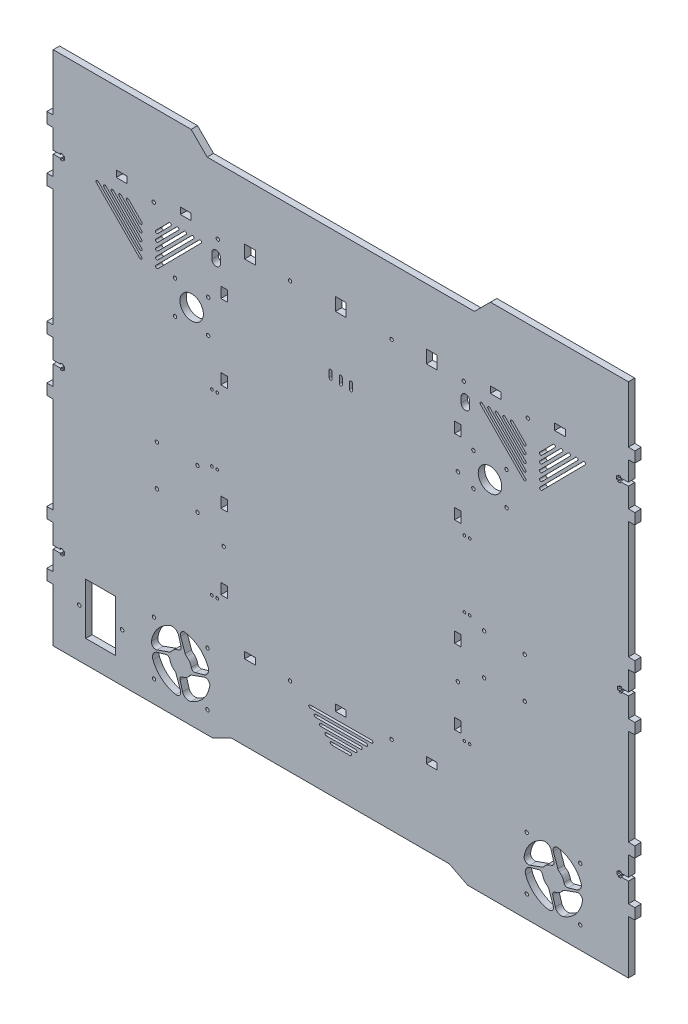
SolidWorks part; units mm, degrees
material "Клен"
ref_plane "Front" through (0, 0, 0) normal (0, 0, 1) x (1, 0, 0)
ref_plane "Top" through (0, 0, 0) normal (0, 1, 0) x (1, 0, 0)
ref_plane "Right" through (0, 0, 0) normal (1, 0, 0) x (0, 0, -1)
sketch "Эскиз1" plane through (0, 0, 0) normal (0, 0, 1) x (1, 0, 0)
  line L3 (1048.7554, 41.5559) -> (1198.2753, 41.5559)
  line L12 (1586.7554, 42.2299) -> (1586.7554, 41.5559)
  line L13 (1397.7554, 444.5559) -> (1407.7554, 444.5559)
  line L14 (1407.7554, 444.5559) -> (1407.7554, 456.6559)
  line L15 (1407.7554, 456.6559) -> (1397.7554, 456.6559)
  line L16 (1397.7554, 456.6559) -> (1397.7554, 444.5559)
  line L17 (1048.7554, 42.2256) -> (1048.7554, 41.5559)
  line L18 (1197.1554, 434.4743) -> (1197.1554, 429.1914)
  line L19 (1503.9666, 426.2291) -> (1516.2724, 438.6716)
  line L20 (1546.3337, 437.0699) -> (1505.9003, 396.1873)
  line L21 (1227.7554, 444.5559) -> (1237.7554, 444.5559)
  line L22 (1237.7554, 444.5559) -> (1237.7554, 456.6559)
  line L23 (1237.7554, 456.6559) -> (1227.7554, 456.6559)
  line L24 (1227.7554, 456.6559) -> (1227.7554, 444.5559)
  line L25 (1312.7554, 444.5559) -> (1322.7554, 444.5559)
  line L26 (1322.7554, 444.5559) -> (1322.7554, 456.6559)
  line L27 (1322.7554, 456.6559) -> (1312.7554, 456.6559)
  line L28 (1312.7554, 456.6559) -> (1312.7554, 444.5559)
  line L38 (1525.1209, 436.9527) -> (1505.7831, 417.4001)
  line L41 (1504.0838, 405.0162) -> (1537.4853, 438.7888)
  line L43 (1504.1228, 397.9452) -> (1544.5562, 438.8279)
  line L44 (1504.0056, 419.1581) -> (1523.3433, 438.7107)
  line L48 (1167.7554, 450.5559) -> (1177.7554, 450.5559)
  line L49 (1177.7554, 450.5559) -> (1177.7554, 456.6559)
  line L50 (1177.7554, 456.6559) -> (1167.7554, 456.6559)
  line L51 (1167.7554, 456.6559) -> (1167.7554, 450.5559)
  line L52 (1518.0499, 436.9136) -> (1505.7441, 424.4711)
  line L53 (1532.1918, 436.9918) -> (1505.8222, 410.3292)
  line L54 (1539.2628, 437.0308) -> (1505.8613, 403.2582)
  line L55 (1504.0447, 412.0872) -> (1530.4143, 438.7498)
  line L56 (1457.7554, 450.5559) -> (1467.7554, 450.5559)
  line L57 (1467.7554, 450.5559) -> (1467.7554, 456.6559)
  line L58 (1467.7554, 456.6559) -> (1457.7554, 456.6559)
  line L59 (1457.7554, 456.6559) -> (1457.7554, 450.5559)
  line L78 (1131.3881, 397.9452) -> (1090.9547, 438.8279)
  line L80 (1089.1772, 437.0699) -> (1129.6105, 396.1873)
  line L82 (1096.2481, 437.0308) -> (1129.6496, 403.2582)
  line L83 (1131.4271, 405.0162) -> (1098.0256, 438.7888)
  line L84 (1131.4662, 412.0872) -> (1105.0966, 438.7498)
  line L85 (1103.3191, 436.9918) -> (1129.6887, 410.3292)
  line L86 (1131.5052, 419.1581) -> (1112.1675, 438.7107)
  line L87 (1110.39, 436.9527) -> (1129.7277, 417.4001)
  line L88 (1131.5443, 426.2291) -> (1119.2385, 438.6716)
  line L89 (1117.461, 436.9136) -> (1129.7668, 424.4711)
  line L90 (1144.921, 397.9452) -> (1185.3543, 438.8279)
  line L91 (1187.1318, 437.0699) -> (1146.6985, 396.1873)
  line L92 (1397.7554, 120.5559) -> (1407.7554, 120.5559)
  line L93 (1407.7554, 120.5559) -> (1407.7554, 126.6559)
  line L94 (1407.7554, 126.6559) -> (1397.7554, 126.6559)
  line L95 (1397.7554, 126.6559) -> (1397.7554, 120.5559)
  line L96 (1312.7554, 120.5559) -> (1322.7554, 120.5559)
  line L97 (1322.7554, 120.5559) -> (1322.7554, 126.6559)
  line L98 (1322.7554, 126.6559) -> (1312.7554, 126.6559)
  line L99 (1312.7554, 126.6559) -> (1312.7554, 120.5559)
  line L100 (1227.7554, 120.5559) -> (1237.7554, 120.5559)
  line L101 (1237.7554, 120.5559) -> (1237.7554, 126.6559)
  line L102 (1237.7554, 126.6559) -> (1227.7554, 126.6559)
  line L143 (1227.7554, 126.6559) -> (1227.7554, 120.5559)
  line L148 (1079.1628, 110.8776) -> (1079.1628, 62.8776)
  line L154 (1455.45, 437.0308) -> (1488.8515, 403.2582)
  line L159 (1107.1628, 110.8776) -> (1079.1628, 110.8776)
  line L160 (1079.1628, 62.8776) -> (1107.1628, 62.8776)
  line L161 (1107.1628, 62.8776) -> (1107.1628, 110.8776)
  line L162 (1144.8819, 405.0162) -> (1178.2834, 438.7888)
  line L163 (1180.0609, 437.0308) -> (1146.6594, 403.2582)
  line L164 (1172.9899, 436.9918) -> (1146.6203, 410.3292)
  line L165 (1144.8428, 412.0872) -> (1171.2124, 438.7498)
  line L166 (1144.8038, 419.1581) -> (1164.1415, 438.7107)
  line L167 (1165.919, 436.9527) -> (1146.5813, 417.4001)
  line L168 (1158.848, 436.9136) -> (1146.5422, 424.4711)
  line L169 (1144.7647, 426.2291) -> (1157.0705, 438.6716)
  line L170 (1205.1554, 429.1914) -> (1205.1554, 434.4743)
  line L171 (1430.3554, 429.1914) -> (1430.3554, 434.4743)
  line L172 (1326.6292, 91.6177) -> (1309.1294, 91.521)
  line L173 (1309.1156, 94.021) -> (1326.6154, 94.1176)
  line L174 (1331.6015, 96.6452) -> (1304.1019, 96.4933)
  line L175 (1304.0881, 98.9933) -> (1331.5877, 99.1452)
  line L176 (1336.5738, 101.6728) -> (1299.0744, 101.4656)
  line L177 (1299.0605, 103.9656) -> (1336.56, 104.1727)
  line L178 (1289.0054, 113.9102) -> (1346.5046, 114.2278)
  line L179 (1346.5184, 111.7279) -> (1289.0193, 111.4102)
  line L180 (1341.5461, 106.7003) -> (1294.0468, 106.4379)
  line L181 (1294.033, 108.9379) -> (1341.5323, 109.2003)
  line L182 (1490.629, 405.0162) -> (1457.2275, 438.7888)
  line L183 (1448.379, 437.0699) -> (1488.8124, 396.1873)
  line L184 (1469.5919, 436.9527) -> (1488.9296, 417.4001)
  line L185 (1476.6629, 436.9136) -> (1488.9687, 424.4711)
  line L186 (1490.5899, 397.9452) -> (1450.1565, 438.8279)
  line L187 (1490.7071, 419.1581) -> (1471.3694, 438.7107)
  line L188 (1462.521, 436.9918) -> (1488.8906, 410.3292)
  line L189 (1490.7462, 426.2291) -> (1478.4404, 438.6716)
  line L198 (1530.3174, 86.3769) -> (1538.4752, 88.7337)
  line L199 (1494.5571, 86.9094) -> (1506.2002, 91.0661)
  line L200 (1517.0418, 100.6255) -> (1514.685, 108.7833)
  line L201 (1502.7664, 87.3542) -> (1494.6086, 84.9974)
  line L202 (1538.538, 86.8062) -> (1526.8948, 82.6495)
  line L203 (1516.0532, 73.09) -> (1518.4101, 64.9322)
  line L204 (1516.4826, 64.8695) -> (1512.3258, 76.5127)
  line L205 (1516.6012, 108.8616) -> (1520.758, 97.2184)
  line L210 (1215.2753, 50.2559) -> (1198.2753, 41.5559)
  line L268 (1215.2753, 50.2559) -> (1419.2753, 50.2559)
  line L269 (1419.2753, 50.2559) -> (1436.2753, 41.5559)
  line L270 (1436.2753, 41.5559) -> (1586.7554, 41.5559)
  line L271 (1490.6681, 412.0872) -> (1464.2985, 438.7498)
  line L302 (1527.7554, 456.6559) -> (1517.7554, 456.6559)
  line L303 (1517.7554, 450.5559) -> (1527.7554, 450.5559)
  line L304 (1517.7554, 456.6559) -> (1517.7554, 450.5559)
  line L305 (1527.7554, 450.5559) -> (1527.7554, 456.6559)
  line L306 (1117.7554, 450.5559) -> (1117.7554, 456.6559)
  line L307 (1107.7554, 456.6559) -> (1107.7554, 450.5559)
  line L308 (1117.7554, 456.6559) -> (1107.7554, 456.6559)
  line L309 (1107.7554, 450.5559) -> (1117.7554, 450.5559)
  line L310 (1167.825, 64.8695) -> (1163.6683, 76.5127)
  line L331 (1438.3554, 434.4743) -> (1438.3554, 429.1914)
  line L332 (1592.7554, 85.0176) -> (1592.7554, 537.1765) construction
  line L333 (989.7428, 524.5559) -> (1177.7554, 524.5559) construction
  line L335 (1048.7554, 524.5559) -> (1177.7554, 524.5559)
  line L337 (1048.7554, 524.5559) -> (1048.7554, 471.6559)
  line L338 (1586.7554, 524.5559) -> (1586.7554, 471.6484)
  line L339 (1442.7554, 509.5559) -> (1457.7554, 524.5559)
  line L342 (1192.7554, 509.5559) -> (1442.7554, 509.5559)
  line L346 (1192.7554, 509.5559) -> (1177.7554, 524.5559)
  line L348 (1592.7554, 461.5645) -> (1586.7554, 461.472)
  line L349 (1457.7554, 524.5559) -> (1617.7234, 524.5559) construction
  line L350 (1457.7554, 524.5559) -> (1586.7554, 524.5559)
  line L358 (1059.2554, 440.0059) -> (1059.2554, 443.1059)
  line L359 (1057.7554, 438.8059) -> (1057.7554, 440.0059)
  line L361 (1057.7554, 270.0059) -> (1059.2554, 270.0059)
  line L362 (1055.5554, 270.0059) -> (1055.5554, 268.8059)
  line L363 (1430.3554, 401.4559) -> (1430.3554, 411.4559)
  line L364 (1430.3554, 411.4559) -> (1424.2554, 411.4559)
  line L365 (1424.2554, 411.4559) -> (1424.2554, 401.4559)
  line L366 (1424.2554, 401.4559) -> (1430.3554, 401.4559)
  line L367 (1430.3554, 331.4559) -> (1430.3554, 341.4559)
  line L368 (1430.3554, 341.4559) -> (1424.2554, 341.4559)
  line L369 (1424.2554, 341.4559) -> (1424.2554, 331.4559)
  line L370 (1424.2554, 331.4559) -> (1430.3554, 331.4559)
  line L371 (1430.3554, 231.4559) -> (1430.3554, 241.4559)
  line L372 (1430.3554, 241.4559) -> (1424.2554, 241.4559)
  line L373 (1424.2554, 241.4559) -> (1424.2554, 231.4559)
  line L374 (1424.2554, 231.4559) -> (1430.3554, 231.4559)
  line L375 (1424.2554, 171.4559) -> (1424.2554, 161.4559)
  line L376 (1424.2554, 161.4559) -> (1430.3554, 161.4559)
  line L377 (1430.3554, 161.4559) -> (1430.3554, 171.4559)
  line L378 (1430.3554, 171.4559) -> (1424.2554, 171.4559)
  line L379 (1205.5754, 161.4559) -> (1211.6754, 161.4559)
  line L380 (1211.6754, 161.4559) -> (1211.6754, 171.4559)
  line L381 (1205.5754, 171.4559) -> (1205.5754, 161.4559)
  line L382 (1211.6754, 171.4559) -> (1205.5754, 171.4559)
  line L383 (1211.6754, 231.4559) -> (1211.6754, 241.4559)
  line L384 (1211.6754, 241.4559) -> (1205.5754, 241.4559)
  line L385 (1205.5754, 241.4559) -> (1205.5754, 231.4559)
  line L386 (1205.5754, 231.4559) -> (1211.6754, 231.4559)
  line L387 (1205.5754, 331.4559) -> (1211.6754, 331.4559)
  line L388 (1211.6754, 331.4559) -> (1211.6754, 341.4559)
  line L389 (1205.5754, 341.4559) -> (1205.5754, 331.4559)
  line L390 (1211.6754, 341.4559) -> (1205.5754, 341.4559)
  line L391 (1205.5754, 401.4559) -> (1211.6754, 401.4559)
  line L392 (1211.6754, 401.4559) -> (1211.6754, 411.4559)
  line L393 (1211.6754, 411.4559) -> (1205.5754, 411.4559)
  line L394 (1205.5754, 411.4559) -> (1205.5754, 401.4559)
  line L395 (1145.8995, 86.9094) -> (1157.5427, 91.0661)
  line L396 (1189.8804, 86.8062) -> (1178.2373, 82.6495)
  line L397 (1167.3957, 73.09) -> (1169.7525, 64.9322)
  line L398 (1154.1089, 87.3542) -> (1145.951, 84.9974)
  line L399 (1181.6599, 86.3769) -> (1189.8177, 88.7337)
  line L400 (1167.9437, 108.8616) -> (1172.1004, 97.2184)
  line L414 (1057.7554, 118.8059) -> (1057.7554, 120.0059)
  line L415 (1168.3843, 100.6255) -> (1166.0274, 108.7833)
  line L416 (1317.7554, 12.4246) -> (1317.7554, 537.1765) construction
  line L417 (1586.7554, 537.1765) -> (1586.7554, 12.4246) construction
  line L418 (1048.7554, 537.1765) -> (1048.7554, -11.6164) construction
  line L419 (1042.7554, 91.5559) -> (1042.7554, 101.5559)
  line L422 (1048.7554, 123.1059) -> (1048.7554, 141.4559)
  line L426 (1059.2554, 123.1059) -> (1057.7554, 123.1059)
  line L427 (1057.7554, 274.3059) -> (1055.5554, 274.3059)
  line L428 (1325.8554, 394.0442) -> (1325.8554, 388.0442)
  line L429 (1328.6554, 388.0442) -> (1328.6554, 394.0442)
  line L430 (1042.7554, 101.5559) -> (1048.7554, 101.6559)
  line L431 (1057.7554, 120.0059) -> (1059.2554, 120.0059)
  line L432 (1316.3554, 394.0442) -> (1316.3554, 388.0442)
  line L433 (1319.1554, 388.0442) -> (1319.1554, 394.0442)
  line L434 (1042.7554, 141.5559) -> (1042.7554, 151.5559)
  line L435 (1042.7554, 301.5559) -> (1048.7554, 301.6559)
  line L436 (1306.8554, 394.0442) -> (1306.8554, 388.0442)
  line L437 (1309.6554, 388.0442) -> (1309.6554, 394.0442)
  line L438 (1055.5554, 120.0059) -> (1055.5554, 118.8059)
  line L439 (1048.7554, 411.4559) -> (1042.7554, 411.5559)
  line L440 (1055.5554, 444.3059) -> (1055.5554, 443.1059)
  line L441 (1057.7554, 124.3059) -> (1055.5554, 124.3059)
  line L442 (1055.5554, 443.1059) -> (1048.7554, 443.1059)
  line L443 (1048.7554, 120.0059) -> (1055.5554, 120.0059)
  line L444 (1042.7554, 241.5559) -> (1042.7554, 251.5559)
  line L445 (1055.5554, 268.8059) -> (1057.7554, 268.8059)
  line L446 (1055.5554, 274.3059) -> (1055.5554, 273.1059)
  line L447 (1048.7554, 461.4559) -> (1042.7554, 461.5559)
  line L448 (1048.7554, 101.6559) -> (1048.7554, 120.0059)
  line L449 (1057.7554, 440.0059) -> (1059.2554, 440.0059)
  line L450 (1048.7554, 251.6559) -> (1048.7554, 270.0059)
  line L451 (1042.7554, 291.5559) -> (1042.7554, 301.5559)
  line L452 (1042.7554, 471.5559) -> (1048.7554, 471.6559)
  line L453 (1059.2554, 443.1059) -> (1057.7554, 443.1059)
  line L454 (1048.7554, 42.2256) -> (1048.7554, 91.4559)
  line L455 (1048.7554, 273.1059) -> (1048.7554, 291.4559)
  line L456 (1055.5554, 440.0059) -> (1055.5554, 438.8059)
  line L457 (1055.5554, 438.8059) -> (1057.7554, 438.8059)
  line L458 (1042.7554, 421.5559) -> (1048.7554, 421.6559)
  line L459 (1048.7554, 443.1059) -> (1048.7554, 461.4559)
  line L460 (1048.7554, 141.4559) -> (1042.7554, 141.5559)
  line L461 (1048.7554, 301.6559) -> (1048.7554, 411.4559)
  line L462 (1048.7554, 91.4559) -> (1042.7554, 91.5559)
  line L463 (1048.7554, 270.0059) -> (1055.5554, 270.0059)
  line L464 (1048.7554, 291.4559) -> (1042.7554, 291.5559)
  line L465 (1059.2554, 120.0059) -> (1059.2554, 123.1059)
  line L466 (1057.7554, 273.1059) -> (1057.7554, 274.3059)
  line L467 (1042.7554, 251.5559) -> (1048.7554, 251.6559)
  line L468 (1059.2554, 273.1059) -> (1057.7554, 273.1059)
  line L469 (1048.7554, 421.6559) -> (1048.7554, 440.0059)
  line L470 (1042.7554, 461.5559) -> (1042.7554, 471.5559)
  line L471 (1057.7554, 268.8059) -> (1057.7554, 270.0059)
  line L472 (1057.7554, 443.1059) -> (1057.7554, 444.3059)
  line L473 (1042.7554, 151.5559) -> (1048.7554, 151.6559)
  line L474 (1059.2554, 270.0059) -> (1059.2554, 273.1059)
  line L475 (1055.5554, 273.1059) -> (1048.7554, 273.1059)
  line L476 (1048.7554, 151.6559) -> (1048.7554, 241.4559)
  line L477 (1057.7554, 444.3059) -> (1055.5554, 444.3059)
  line L478 (1055.5554, 124.3059) -> (1055.5554, 123.1059)
  line L479 (1048.7554, 241.4559) -> (1042.7554, 241.5559)
  line L480 (1055.5554, 123.1059) -> (1048.7554, 123.1059)
  line L481 (1057.7554, 123.1059) -> (1057.7554, 124.3059)
  line L482 (1055.5554, 118.8059) -> (1057.7554, 118.8059)
  line L483 (1042.7554, 411.5559) -> (1042.7554, 421.5559)
  line L484 (1048.7554, 440.0059) -> (1055.5554, 440.0059)
  line L488 (1586.7554, 301.6559) -> (1592.7554, 301.5559)
  line L489 (1592.7554, 251.5803) -> (1592.7554, 241.5722)
  line L490 (1579.2472, 444.3102) -> (1577.0472, 444.3102)
  line L491 (1592.7554, 471.5559) -> (1592.7554, 461.5645)
  line L492 (1579.9554, 120.0141) -> (1586.7554, 120.0141)
  line L493 (1592.7554, 101.5641) -> (1592.7554, 91.5559)
  line L494 (1579.9554, 123.1141) -> (1579.9554, 124.3141)
  line L496 (1577.7554, 120.0141) -> (1577.7554, 118.8141)
  line L497 (1578.2356, 268.8303) -> (1580.4356, 268.8303)
  line L498 (1575.5472, 440.0102) -> (1577.0472, 440.0102)
  line L499 (1580.4356, 274.3303) -> (1578.2356, 274.3303)
  line L500 (1577.7554, 123.1141) -> (1576.2554, 123.1141)
  line L501 (1576.7356, 273.1303) -> (1576.7356, 270.0303)
  line L502 (1586.0472, 443.1102) -> (1586.7554, 443.1102)
  line L503 (1578.2356, 274.3303) -> (1578.2356, 273.1303)
  line L504 (1577.0472, 438.8102) -> (1579.2472, 438.8102)
  line L505 (1576.2554, 120.0141) -> (1577.7554, 120.0141)
  line L506 (1586.0472, 443.1102) -> (1579.2472, 443.1102)
  line L507 (1586.7554, 141.4641) -> (1586.7554, 123.1141)
  line L508 (1592.7554, 141.5641) -> (1586.7554, 141.4641)
  line L509 (1586.7554, 251.6803) -> (1592.7554, 251.5803)
  line L510 (1578.2356, 270.0303) -> (1578.2356, 268.8303)
  line L511 (1580.4356, 270.0303) -> (1586.7554, 270.0303)
  line L512 (1579.9554, 124.3141) -> (1577.7554, 124.3141)
  line L513 (1577.7554, 124.3141) -> (1577.7554, 123.1141)
  line L514 (1592.7554, 141.5641) -> (1592.7554, 151.5722)
  line L515 (1579.2472, 440.0102) -> (1586.0472, 440.0102)
  line L516 (1592.7554, 411.5559) -> (1586.7554, 411.4559)
  line L517 (1580.4356, 268.8303) -> (1580.4356, 270.0303)
  line L518 (1586.7554, 91.4559) -> (1586.7554, 42.2299)
  line L519 (1592.7554, 241.5722) -> (1586.7554, 241.4722)
  line L520 (1579.2472, 438.8102) -> (1579.2472, 440.0102)
  line L521 (1580.4356, 273.1303) -> (1580.4356, 274.3303)
  line L522 (1586.7554, 270.0303) -> (1586.7554, 251.6803)
  line L523 (1577.0472, 443.1102) -> (1575.5472, 443.1102)
  line L524 (1586.7554, 151.6722) -> (1592.7554, 151.5722)
  line L525 (1577.7554, 118.8141) -> (1579.9554, 118.8141)
  line L526 (1592.7554, 421.5559) -> (1592.7554, 411.5559)
  line L527 (1586.7554, 421.6484) -> (1592.7554, 421.5559)
  line L528 (1579.9554, 118.8141) -> (1579.9554, 120.0141)
  line L529 (1586.7554, 273.1303) -> (1580.4356, 273.1303)
  line L530 (1586.7554, 123.1141) -> (1579.9554, 123.1141)
  line L531 (1586.0472, 440.0102) -> (1586.7554, 440.0102)
  line L532 (1576.7356, 270.0303) -> (1578.2356, 270.0303)
  line L533 (1586.7554, 461.472) -> (1586.7554, 443.1102)
  line L534 (1575.5472, 443.1102) -> (1575.5472, 440.0102)
  line L535 (1592.7554, 291.5478) -> (1586.7554, 291.4478)
  line L536 (1586.7554, 120.0141) -> (1586.7554, 101.6641)
  line L537 (1576.2554, 123.1141) -> (1576.2554, 120.0141)
  line L538 (1586.7554, 101.6641) -> (1592.7554, 101.5641)
  line L539 (1592.7554, 91.5559) -> (1586.7554, 91.4559)
  line L540 (1586.7554, 411.4559) -> (1586.7554, 301.6559)
  line L541 (1592.7554, 301.5559) -> (1592.7554, 291.5478)
  line L542 (1577.0472, 444.3102) -> (1577.0472, 443.1102)
  line L543 (1579.2472, 443.1102) -> (1579.2472, 444.3102)
  line L544 (1586.7554, 241.4722) -> (1586.7554, 151.6722)
  line L545 (1586.7554, 440.0102) -> (1586.7554, 421.6484)
  line L546 (1586.7554, 291.4478) -> (1586.7554, 273.1303)
  line L547 (1578.2356, 273.1303) -> (1576.7356, 273.1303)
  line L548 (1586.7554, 471.6484) -> (1592.7554, 471.5559)
  line L549 (1577.0472, 440.0102) -> (1577.0472, 438.8102)
  circle A0 centre (1193.7068, 365.5072) radius 1.6
  circle A1 centre (1162.7068, 365.5072) radius 1.6
  circle A2 centre (1178.2068, 380.5559) radius 11
  circle A3 centre (1193.7068, 396.5072) radius 1.6
  circle A4 centre (1202.7554, 448.0572) radius 1.6
  circle A5 centre (1432.7554, 448.0572) radius 1.6
  circle A6 centre (1365.2554, 448.0572) radius 1.6
  circle A7 centre (1270.2554, 448.0572) radius 1.6
  circle A12 centre (1162.7068, 396.5072) radius 1.6
  circle A13 centre (1145.7129, 217.2739) radius 1.6
  circle A14 centre (1365.2554, 124.0549) radius 1.6
  circle A15 centre (1270.2554, 124.0549) radius 1.6
  circle A20 centre (1492.7554, 448.0572) radius 1.6
  circle A21 centre (1142.7554, 448.0572) radius 1.6
  circle A24 centre (1073.1628, 86.8776) radius 1.65
  circle A25 centre (1113.1628, 86.8776) radius 1.65
  circle A26 centre (1145.7129, 255.2739) radius 1.6
  circle A27 centre (1183.7129, 217.2739) radius 1.6
  circle A28 centre (1183.7129, 255.2739) radius 1.6
  arc A29 (1504.0056, 419.1581) -> (1505.7831, 417.4001) centre (1504.8944, 418.2791) ccw
  arc A30 (1503.9666, 426.2291) -> (1505.7441, 424.4711) centre (1504.8553, 425.3501) ccw
  arc A31 (1504.1228, 397.9452) -> (1505.9003, 396.1873) centre (1505.0116, 397.0662) ccw
  arc A32 (1518.0499, 436.9136) -> (1516.2724, 438.6716) centre (1517.1611, 437.7926) ccw
  arc A33 (1504.0447, 412.0872) -> (1505.8222, 410.3292) centre (1504.9335, 411.2082) ccw
  arc A34 (1546.3337, 437.0699) -> (1544.5562, 438.8279) centre (1545.445, 437.9489) ccw
  arc A35 (1539.2628, 437.0308) -> (1537.4853, 438.7888) centre (1538.374, 437.9098) ccw
  arc A36 (1326.6292, 91.6177) -> (1326.6154, 94.1176) centre (1326.6223, 92.8677) ccw
  arc A37 (1309.1156, 94.021) -> (1309.1294, 91.521) centre (1309.1225, 92.771) ccw
  arc A38 (1304.0881, 98.9933) -> (1304.1019, 96.4933) centre (1304.095, 97.7433) ccw
  arc A39 (1331.6015, 96.6452) -> (1331.5877, 99.1452) centre (1331.5946, 97.8952) ccw
  arc A40 (1336.5738, 101.6728) -> (1336.56, 104.1727) centre (1336.5669, 102.9228) ccw
  arc A41 (1299.0605, 103.9656) -> (1299.0744, 101.4656) centre (1299.0674, 102.7156) ccw
  arc A42 (1294.033, 108.9379) -> (1294.0468, 106.4379) centre (1294.0399, 107.6879) ccw
  arc A43 (1341.5461, 106.7003) -> (1341.5323, 109.2003) centre (1341.5392, 107.9503) ccw
  arc A44 (1346.5184, 111.7279) -> (1346.5046, 114.2278) centre (1346.5115, 112.9779) ccw
  arc A45 (1289.0054, 113.9102) -> (1289.0193, 111.4102) centre (1289.0124, 112.6602) ccw
  arc A46 (1157.5427, 91.0661) -> (1159.5017, 92.5785) centre (1156.1978, 94.8332) ccw
  arc A47 (1450.1565, 438.8279) -> (1448.379, 437.0699) centre (1449.2678, 437.9489) ccw
  arc A48 (1471.3694, 438.7107) -> (1469.5919, 436.9527) centre (1470.4807, 437.8317) ccw
  arc A49 (1457.2275, 438.7888) -> (1455.45, 437.0308) centre (1456.3388, 437.9098) ccw
  arc A50 (1488.9687, 424.4711) -> (1490.7462, 426.2291) centre (1489.8574, 425.3501) ccw
  arc A51 (1488.8515, 403.2582) -> (1490.629, 405.0162) centre (1489.7403, 404.1372) ccw
  arc A52 (1488.8124, 396.1873) -> (1490.5899, 397.9452) centre (1489.7012, 397.0662) ccw
  arc A53 (1488.8906, 410.3292) -> (1490.6681, 412.0872) centre (1489.7793, 411.2082) ccw
  arc A54 (1488.9296, 417.4001) -> (1490.7071, 419.1581) centre (1489.8184, 418.2791) ccw
  arc A55 (1478.4404, 438.6716) -> (1476.6629, 436.9136) centre (1477.5516, 437.7926) ccw
  arc A56 (1464.2985, 438.7498) -> (1462.521, 436.9918) centre (1463.4097, 437.8708) ccw
  arc A67 (1166.0274, 108.7833) -> (1158.15, 112.7336) centre (1160.2632, 107.118) ccw
  arc A68 (1189.8177, 88.7337) -> (1193.7679, 96.6112) centre (1188.1523, 94.498) ccw
  circle A69 centre (1143.0318, 112.013) radius 1.6
  circle A70 centre (1143.0318, 62.013) radius 1.6
  arc A71 (1166.0477, 96.8429) -> (1168.3843, 100.6255) centre (1165.5021, 99.7929) ccw
  arc A72 (1145.951, 84.9974) -> (1142.0008, 77.1199) centre (1147.6164, 79.2331) ccw
  arc A100 (1178.2373, 82.6495) -> (1176.2782, 81.1371) centre (1179.5822, 78.8823) ccw
  arc A102 (1538.4752, 88.7337) -> (1542.4254, 96.6112) centre (1536.8099, 94.498) ccw
  arc A103 (1526.2875, 60.982) -> (1543.8306, 82.3942) centre (1516.5531, 86.85) ccw
  arc A104 (1512.3258, 76.5127) -> (1510.8135, 78.4717) centre (1508.5587, 75.1677) ccw
  arc A105 (1518.3898, 76.8727) -> (1516.0532, 73.09) centre (1518.9354, 73.9227) ccw
  arc A106 (1489.2645, 91.3213) -> (1494.5571, 86.9094) centre (1493.2122, 90.6765) ccw
  arc A107 (1512.0706, 59.5769) -> (1516.4826, 64.8695) centre (1512.7155, 63.5246) ccw
  arc A108 (1506.2002, 91.0661) -> (1508.1593, 92.5785) centre (1504.8553, 94.8332) ccw
  arc A109 (1521.0132, 114.1542) -> (1516.6012, 108.8616) centre (1520.3684, 110.2065) ccw
  arc A110 (1518.3898, 76.8727) -> (1524.9358, 81.1371) centre (1516.5419, 86.8655) ccw
  circle A111 centre (1541.6893, 112.013) radius 1.6
  arc A112 (1494.6086, 84.9974) -> (1490.6584, 77.1199) centre (1496.2739, 79.2331) ccw
  arc A113 (1506.5491, 85.0176) -> (1510.8135, 78.4717) centre (1516.5419, 86.8655) ccw
  arc A114 (1526.8948, 82.6495) -> (1524.9358, 81.1371) centre (1528.2397, 78.8823) ccw
  circle A115 centre (1541.6893, 62.013) radius 1.6
  arc A116 (1490.6584, 77.1199) -> (1512.0706, 59.5769) centre (1516.5264, 86.8543) ccw
  arc A117 (1514.685, 108.7833) -> (1506.8075, 112.7336) centre (1508.9207, 107.118) ccw
  circle A118 centre (1491.6893, 112.013) radius 1.6
  arc A119 (1520.758, 97.2184) -> (1522.2703, 95.2594) centre (1524.5251, 98.5634) ccw
  arc A120 (1542.4254, 96.6112) -> (1521.0132, 114.1542) centre (1516.5574, 86.8768) ccw
  arc A121 (1526.5348, 88.7135) -> (1522.2703, 95.2594) centre (1516.5419, 86.8655) ccw
  arc A122 (1506.8075, 112.7336) -> (1489.2645, 91.3213) centre (1516.5419, 86.8655) ccw
  arc A123 (1506.5491, 85.0176) -> (1502.7664, 87.3542) centre (1503.5991, 84.4721) ccw
  arc A124 (1514.7052, 96.8429) -> (1508.1593, 92.5785) centre (1516.5531, 86.85) ccw
  arc A125 (1543.8306, 82.3942) -> (1538.538, 86.8062) centre (1539.8829, 83.0391) ccw
  circle A126 centre (1491.6893, 62.013) radius 1.6
  arc A127 (1518.4101, 64.9322) -> (1526.2875, 60.982) centre (1524.1743, 66.5976) ccw
  arc A128 (1526.5348, 88.7135) -> (1530.3174, 86.3769) centre (1529.4848, 89.259) ccw
  arc A129 (1514.7052, 96.8429) -> (1517.0418, 100.6255) centre (1514.1597, 99.7929) ccw
  arc A130 (1157.8915, 85.0176) -> (1154.1089, 87.3542) centre (1154.9415, 84.4721) ccw
  arc A131 (1172.3557, 114.1542) -> (1167.9437, 108.8616) centre (1171.7108, 110.2065) ccw
  arc A132 (1172.1004, 97.2184) -> (1173.6128, 95.2594) centre (1175.8676, 98.5634) ccw
  arc A133 (1177.63, 60.982) -> (1195.173, 82.3942) centre (1167.8956, 86.85) ccw
  arc A134 (1193.7679, 96.6112) -> (1172.3557, 114.1542) centre (1167.8999, 86.8768) ccw
  circle A135 centre (1193.0318, 62.013) radius 1.6
  arc A136 (1166.0477, 96.8429) -> (1159.5017, 92.5785) centre (1167.8956, 86.85) ccw
  arc A137 (1169.7525, 64.9322) -> (1177.63, 60.982) centre (1175.5168, 66.5976) ccw
  arc A138 (1169.7323, 76.8727) -> (1176.2782, 81.1371) centre (1167.8844, 86.8655) ccw
  arc A139 (1177.8772, 88.7135) -> (1173.6128, 95.2594) centre (1167.8844, 86.8655) ccw
  arc A160 (1169.7323, 76.8727) -> (1167.3957, 73.09) centre (1170.2778, 73.9227) ccw
  arc A161 (1157.8915, 85.0176) -> (1162.1559, 78.4717) centre (1167.8844, 86.8655) ccw
  arc A162 (1163.4131, 59.5769) -> (1167.825, 64.8695) centre (1164.0579, 63.5246) ccw
  arc A163 (1142.0008, 77.1199) -> (1163.4131, 59.5769) centre (1167.8688, 86.8543) ccw
  arc A164 (1163.6683, 76.5127) -> (1162.1559, 78.4717) centre (1159.9012, 75.1677) ccw
  arc A165 (1195.173, 82.3942) -> (1189.8804, 86.8062) centre (1191.2253, 83.0391) ccw
  arc A166 (1177.8772, 88.7135) -> (1181.6599, 86.3769) centre (1180.8272, 89.259) ccw
  circle A167 centre (1193.0318, 112.013) radius 1.6
  arc A168 (1158.15, 112.7336) -> (1140.6069, 91.3213) centre (1167.8844, 86.8655) ccw
  arc A169 (1140.6069, 91.3213) -> (1145.8995, 86.9094) centre (1144.5546, 90.6765) ccw
  arc A190 (1532.1918, 436.9918) -> (1530.4143, 438.7498) centre (1531.3031, 437.8708) ccw
  arc A191 (1525.1209, 436.9527) -> (1523.3433, 438.7107) centre (1524.2321, 437.8317) ccw
  arc A192 (1504.0838, 405.0162) -> (1505.8613, 403.2582) centre (1504.9725, 404.1372) ccw
  arc A193 (1089.1772, 437.0699) -> (1090.9547, 438.8279) centre (1090.0659, 437.9489) cw
  circle A194 centre (1427.3054, 371.9072) radius 1.6
  circle A195 centre (1427.3054, 201.9072) radius 1.6
  circle A196 centre (1208.2054, 201.9072) radius 1.6
  arc A198 (1131.3881, 397.9452) -> (1129.6105, 396.1873) centre (1130.4993, 397.0662) cw
  arc A199 (1131.4271, 405.0162) -> (1129.6496, 403.2582) centre (1130.5384, 404.1372) cw
  arc A200 (1096.2481, 437.0308) -> (1098.0256, 438.7888) centre (1097.1369, 437.9098) cw
  arc A201 (1103.3191, 436.9918) -> (1105.0966, 438.7498) centre (1104.2078, 437.8708) cw
  arc A202 (1131.4662, 412.0872) -> (1129.6887, 410.3292) centre (1130.5774, 411.2082) cw
  arc A203 (1110.39, 436.9527) -> (1112.1675, 438.7107) centre (1111.2788, 437.8317) cw
  arc A216 (1131.5052, 419.1581) -> (1129.7277, 417.4001) centre (1130.6165, 418.2791) cw
  arc A217 (1117.461, 436.9136) -> (1119.2385, 438.6716) centre (1118.3497, 437.7926) cw
  arc A218 (1131.5443, 426.2291) -> (1129.7668, 424.4711) centre (1130.6556, 425.3501) cw
  arc A219 (1146.6985, 396.1873) -> (1144.921, 397.9452) centre (1145.8097, 397.0662) cw
  circle A220 centre (1202.1959, 261.1916) radius 1.25
  circle A221 centre (1197.2245, 261.2595) radius 1.25
  circle A228 centre (1202.1586, 156.838) radius 1.25
  circle A229 centre (1197.1872, 156.9059) radius 1.25
  arc A230 (1185.3543, 438.8279) -> (1187.1318, 437.0699) centre (1186.2431, 437.9489) cw
  arc A231 (1178.2834, 438.7888) -> (1180.0609, 437.0308) centre (1179.1721, 437.9098) cw
  circle A232 centre (1438.3088, 156.7702) radius 1.25
  arc A233 (1146.6594, 403.2582) -> (1144.8819, 405.0162) centre (1145.7706, 404.1372) cw
  circle A234 centre (1433.3374, 156.838) radius 1.25
  arc A235 (1171.2124, 438.7498) -> (1172.9899, 436.9918) centre (1172.1012, 437.8708) cw
  arc A237 (1146.6203, 410.3292) -> (1144.8428, 412.0872) centre (1145.7316, 411.2082) cw
  arc A239 (1146.5813, 417.4001) -> (1144.8038, 419.1581) centre (1145.6925, 418.2791) cw
  arc A241 (1164.1415, 438.7107) -> (1165.919, 436.9527) centre (1165.0302, 437.8317) cw
  arc A243 (1157.0705, 438.6716) -> (1158.848, 436.9136) centre (1157.9593, 437.7926) cw
  arc A245 (1146.5422, 424.4711) -> (1144.7647, 426.2291) centre (1145.6534, 425.3501) cw
  circle A247 centre (1472.8041, 365.5072) radius 1.6
  circle A248 centre (1438.3461, 261.1238) radius 1.25
  circle A249 centre (1441.8041, 365.5072) radius 1.6
  circle A250 centre (1433.3748, 261.1916) radius 1.25
  circle A251 centre (1441.8041, 396.5072) radius 1.6
  circle A252 centre (1438.3268, 323.4135) radius 1.25
  circle A253 centre (1457.3041, 380.5559) radius 11
  circle A254 centre (1433.3554, 323.4814) radius 1.25
  circle A255 centre (1472.8041, 396.5072) radius 1.6
  circle A256 centre (1489.798, 217.2739) radius 1.6
  circle A257 centre (1451.798, 217.2739) radius 1.6
  circle A261 centre (1451.798, 255.2739) radius 1.6
  circle A263 centre (1489.798, 255.2739) radius 1.6
  arc A265 (1201.1554, 438.4743) -> (1197.1554, 434.4743) centre (1201.1554, 434.4743) ccw
  arc A267 (1205.1554, 434.4743) -> (1201.1554, 438.4743) centre (1201.1554, 434.4743) ccw
  arc A269 (1197.1554, 429.1914) -> (1201.1554, 425.1914) centre (1201.1554, 429.1914) ccw
  arc A271 (1201.1554, 425.1914) -> (1205.1554, 429.1914) centre (1201.1554, 429.1914) ccw
  arc A273 (1434.3554, 438.4743) -> (1438.3554, 434.4743) centre (1434.3554, 434.4743) cw
  arc A275 (1430.3554, 434.4743) -> (1434.3554, 438.4743) centre (1434.3554, 434.4743) cw
  arc A277 (1434.3554, 425.1914) -> (1430.3554, 429.1914) centre (1434.3554, 429.1914) cw
  arc A279 (1438.3554, 429.1914) -> (1434.3554, 425.1914) centre (1434.3554, 429.1914) cw
  circle A280 centre (1202.1766, 323.4814) radius 1.25
  circle A282 centre (1197.2052, 323.5492) radius 1.25
  arc A312 (1325.8554, 388.0442) -> (1328.6554, 388.0442) centre (1327.2554, 388.0442) ccw
  arc A313 (1328.6554, 394.0442) -> (1325.8554, 394.0442) centre (1327.2554, 394.0442) ccw
  arc A316 (1316.3554, 388.0442) -> (1319.1554, 388.0442) centre (1317.7554, 388.0442) ccw
  arc A317 (1319.1554, 394.0442) -> (1316.3554, 394.0442) centre (1317.7554, 394.0442) ccw
  arc A320 (1306.8554, 388.0442) -> (1309.6554, 388.0442) centre (1308.2554, 388.0442) ccw
  arc A321 (1309.6554, 394.0442) -> (1306.8554, 394.0442) centre (1308.2554, 394.0442) ccw
  point P31 (1317.7554, 524.5559)
  point P51 (1430.3554, 406.4559)
  dimension "D3" = 269
  dimension "D4" = 15.5
  dimension "D5" = 31
  dimension "D6" = 31
  dimension "D2" = 269
  dimension "D8" = 31
  dimension "D9" = 397.9
  dimension "D1" = 149.5198
  dimension "D7" = 250
  dimension "D10" = 6
  dimension "D11" = 0
  dimension "D12" = 0
  dimension "D13" = 67.9
  dimension "D14" = 0
  dimension "D15" = 0
  dimension "D16" = 0
  dimension "D17" = 0
  dimension "D18" = 0
  dimension "D19" = 0
  dimension "D20" = 45.2
  dimension "D21" = 60
  dimension "D22" = 90
  dimension "D23" = 60
  dimension "D24" = 0
  dimension "D25" = 0
  dimension "D26" = 0
  dimension "D27" = 0
  dimension "D28" = 162.4
  dimension "D29" = 0
  dimension "D30" = 6.1
  dimension "D31" = 6.1
  dimension "D32" = 6.1
  dimension "D33" = 6.1
  dimension "D34" = 0
  dimension "D35" = 0
  dimension "D36" = 6.1
  dimension "D37" = 6.1
  dimension "D38" = 6.1
  dimension "D39" = 6.1
  dimension "D40" = 156.82
  dimension "D41" = 0
  dimension "D42" = 156.82
  dimension "D43" = 156.82
  dimension "D44" = 156.82
extrude "Бобышка-Вытянуть1" add sketch "Эскиз1" against normal blind 6
